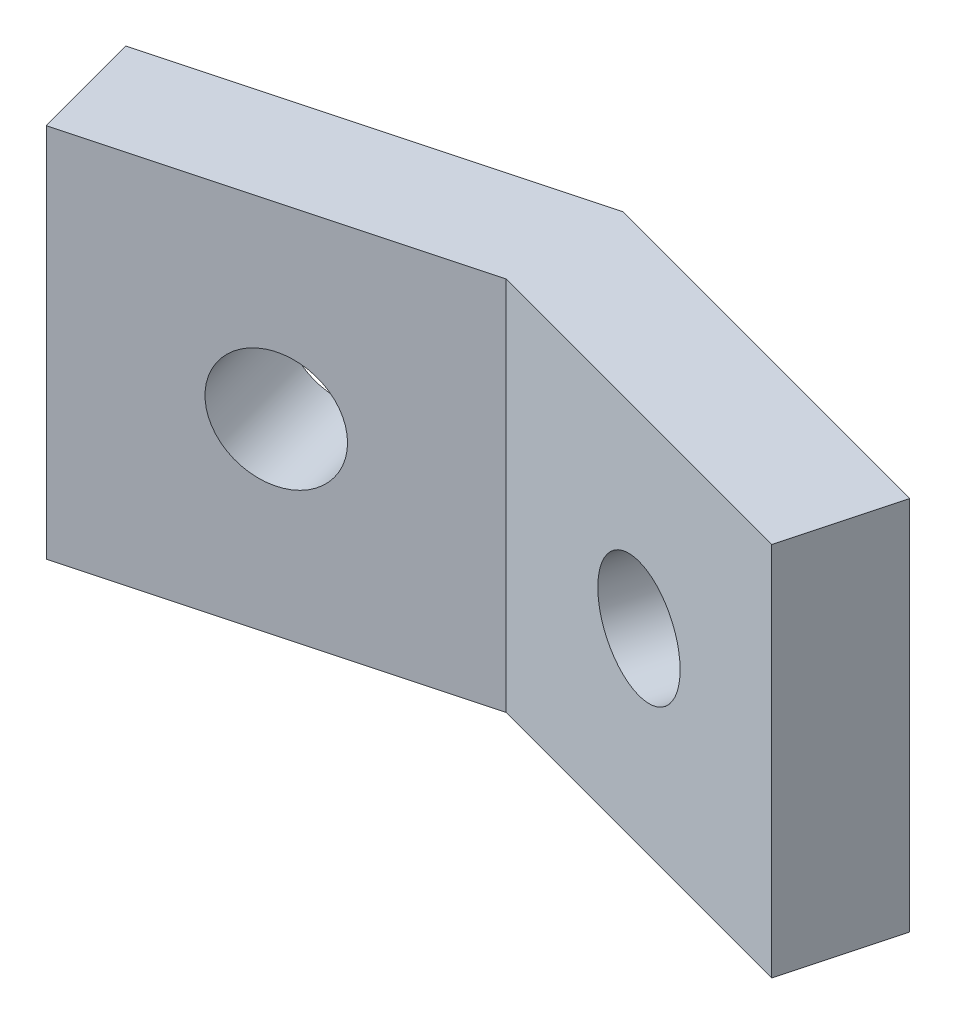
SolidWorks part; units mm, degrees
ref_plane "Front Plane" through (0, 0, 0) normal (0, 0, 1) x (1, 0, 0)
ref_plane "Top Plane" through (0, 0, 0) normal (0, 1, 0) x (1, 0, 0)
ref_plane "Right Plane" through (0, 0, 0) normal (1, 0, 0) x (0, 0, -1)
sketch "Sketch1" plane through (0, 0, 0) normal (0, 1, 0) x (1, 0, 0)
  line L0 (0, -8.6095) -> (0, 20.0112) construction
  line L1 (0, 0) -> (77.0066, -20.6339) construction
  line L2 (0, 1.5529) -> (-10.4357, -1.2433)
  line L4 (0, 1.5529) -> (10.4357, -1.2433)
  line L5 (10.4357, -1.2433) -> (9.6593, -4.1411)
  line L6 (9.6593, -4.1411) -> (0, -1.5529)
  line L10 (-10.4357, -1.2433) -> (-9.6593, -4.1411)
  line L11 (-9.6593, -4.1411) -> (0, -1.5529)
  point P9 (-3.4562, 3.5143)
  dimension "D1" = 105
  dimension "D3" = 3
  dimension "D4" = 10
extrude "Boss-Extrude1" add sketch "Sketch1" along normal blind 10
sketch "Sketch5" plane through (0.3882, 0, 1.4489) normal (0.2588, 0, 0.9659) x (0.9659, 0, -0.2588)
  line L0 (-10.4019, 5) -> (-0.4019, 5) construction
  line L1 (-10.4019, 10) -> (-10.4019, 0) construction
  line L2 (-0.4019, 10) -> (-0.4019, 0) construction
  circle A0 centre (-5.4019, 5) radius 1.55
  dimension "D1" = 3.1
extrude "Cut-Extrude3" cut sketch "Sketch5" against normal blind 10
sketch "Sketch6" plane through (-0.3882, 0, 1.4489) normal (-0.2588, 0, 0.9659) x (0.9659, 0, 0.2588)
  line L0 (0.4019, 5) -> (10.4019, 5) construction
  line L1 (0.4019, 10) -> (0.4019, 0) construction
  line L2 (10.4019, 10) -> (10.4019, 0) construction
  circle A0 centre (5.4019, 5) radius 1.55
  dimension "D1" = 3.1
extrude "Cut-Extrude4" cut sketch "Sketch6" against normal blind 10
